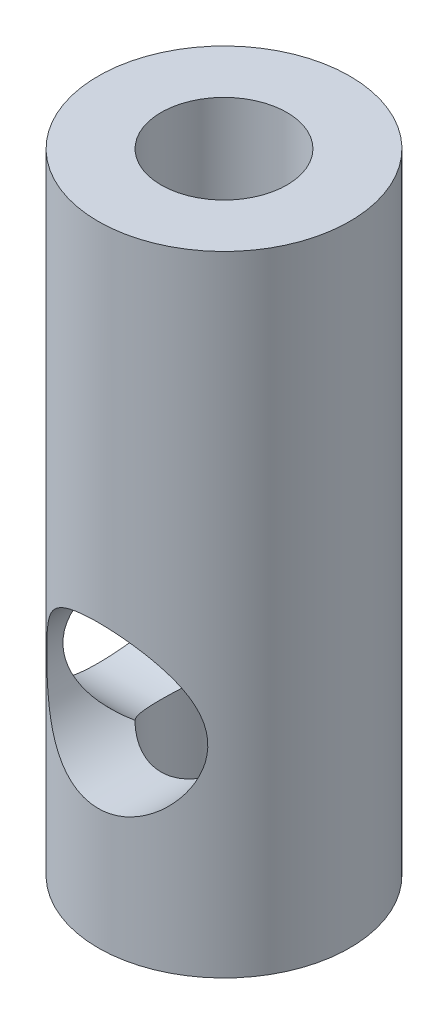
SolidWorks part; units mm, degrees
material "6061 Alloy"
ref_plane "Front Plane" through (0, 0, 0) normal (0, 0, 1) x (1, 0, 0)
ref_plane "Top Plane" through (0, 0, 0) normal (0, 1, 0) x (1, 0, 0)
ref_plane "Right Plane" through (0, 0, 0) normal (1, 0, 0) x (0, 0, -1)
sketch "Sketch1" plane through (0, 0, 0) normal (0, 1, 0) x (1, 0, 0)
  circle A0 centre (0, 0) radius 1.5875
  circle A1 centre (0, 0) radius 3.175
  dimension "D1" = 6.35
  dimension "D2" = 3.175
extrude "Boss-Extrude1" add sketch "Sketch1" along normal blind 15.875
sketch "Sketch2" plane through (0, 0, 0) normal (1, 0, 0) x (0, 0, -1)
  circle A0 centre (0, 5.08) radius 2.032
  point P0 (0, 5.08)
  dimension "D2" = 4.064
  dimension "D1" = 5.08
extrude "Cut-Extrude1" cut sketch "Sketch2" against normal through all
pattern_circular "CirPattern1" count 2 every 90 about axis through (0, 0, 0) along (0, 1, 0) of "Cut-Extrude1"
